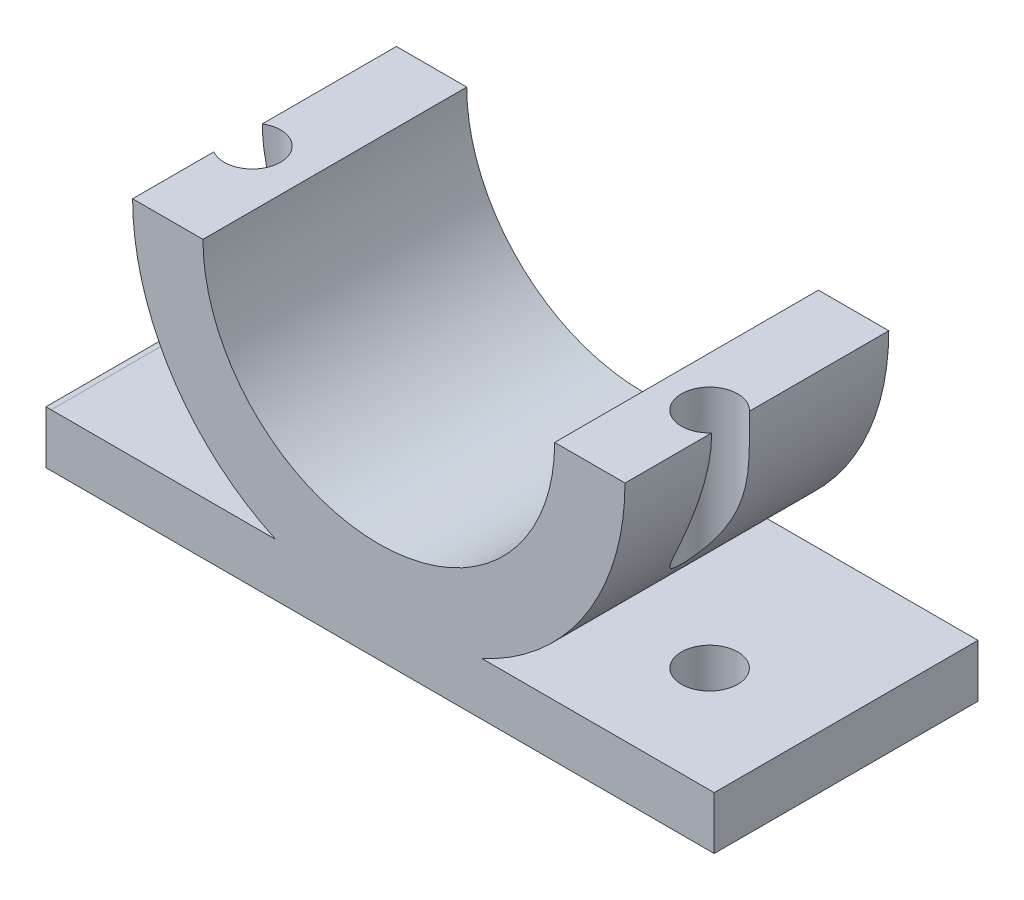
SolidWorks part; units mm, degrees
ref_plane "前视基准面" through (0, 0, 0) normal (0, 0, 1) x (1, 0, 0)
ref_plane "上视基准面" through (0, 0, 0) normal (0, 1, 0) x (1, 0, 0)
ref_plane "右视基准面" through (0, 0, 0) normal (1, 0, 0) x (0, 0, -1)
sketch "草图1" plane through (0, 0, 0) normal (0, 0, 1) x (1, 0, 0)
  line L9 (0, -3.6269) -> (0, 0) construction
  line L13 (-18.6319, -12.7106) -> (-18.9259, -12.7055)
  line L14 (-18.9259, -12.7055) -> (-18.9259, -15.7106)
  line L15 (-18.9259, -15.7106) -> (19.0741, -15.7106)
  line L16 (19.0741, -15.7106) -> (19.0741, -12.7106)
  line L17 (19.0741, -12.7106) -> (5.8685, -12.7106)
  line L18 (-14, 0) -> (-10, 0)
  line L19 (10, 0) -> (14, 0)
  line L20 (-5.8685, -12.7106) -> (-18.6319, -12.7106)
  arc A0 (-14, 0) -> (-5.8685, -12.7106) centre (0, 0) ccw
  arc A1 (-10, 0) -> (10, 0) centre (0, 0) ccw
  arc A2 (5.8685, -12.7106) -> (14, 0) centre (0, 0) ccw
  dimension "D1" = 3
  dimension "D2" = 20
  dimension "D3" = 14
  dimension "D4" = 38
extrude "凸台-拉伸1" add sketch "草图1" along normal blind 15
sketch "草图2" plane through (0, -12.7106, 0) normal (0, 1, 0) x (1, 0, 0)
  circle A0 centre (-13.1901, -9) radius 1.6 construction
  circle A1 centre (12.8099, -9) radius 1.6 construction
  circle A2 centre (-13.1901, -9) radius 1.6
  circle A3 centre (12.8099, -9) radius 1.6
extrude "切除-拉伸1" cut sketch "草图2" against normal through all both and the other way through all
